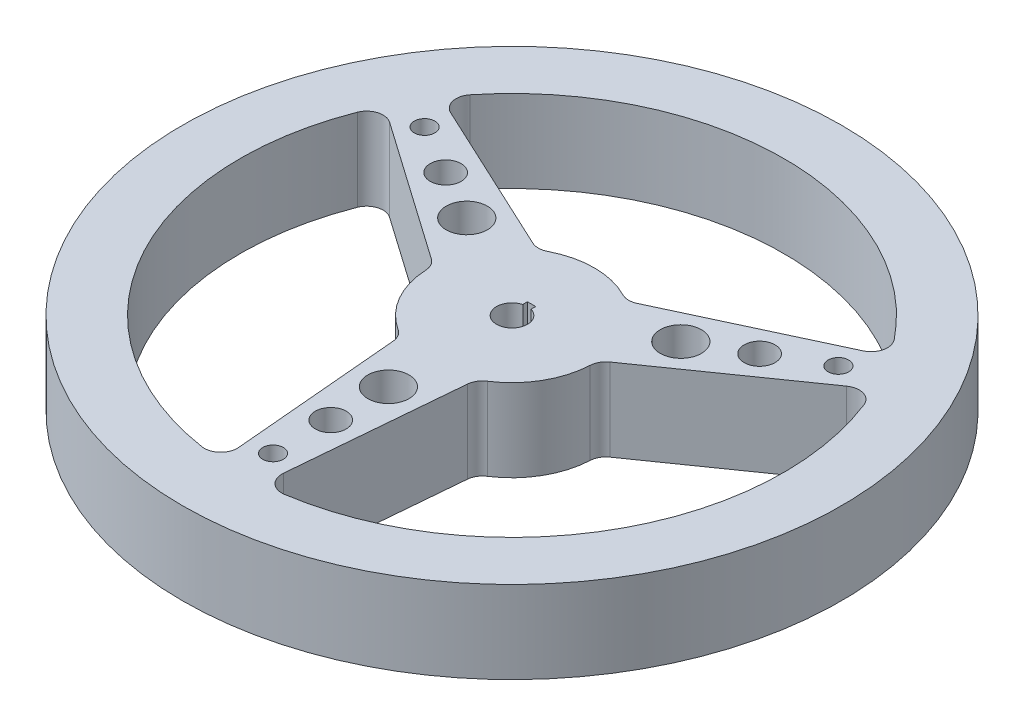
SolidWorks part; units mm, degrees
ref_plane "Front Plane" through (0, 0, 0) normal (0, 0, 1) x (1, 0, 0)
ref_plane "Top Plane" through (0, 0, 0) normal (0, 1, 0) x (1, 0, 0)
ref_plane "Right Plane" through (0, 0, 0) normal (1, 0, 0) x (0, 0, -1)
sketch "Sketch1" plane through (0, 0, 0) normal (0, 1, 0) x (1, 0, 0)
  line L0 (0, 0) -> (0, 3.0163) construction
  line L2 (-0.635, 2.295) -> (-0.635, 3.0163)
  line L3 (-0.635, 3.0163) -> (0.635, 3.0163)
  line L4 (0.635, 2.295) -> (0.635, 3.0163)
  circle A0 centre (0, 0) radius 50.8
  arc A1 (-0.635, 2.295) -> (0.635, 2.295) centre (0, 0) ccw
  dimension "D1" = 101.6
  dimension "D2" = 4.7625
  dimension "D4" = 1.27
  dimension "D5" = 3.0163
extrude "Boss-Extrude1" add sketch "Sketch1" along normal blind 12.7
sketch "Sketch2" plane through (0, 12.7, 0) normal (0, 1, 0) x (1, 0, 0)
  line L0 (3.175, -41.7896) -> (5.8447, -11.2752)
  line L1 (0, 0) -> (0, 33.1089) construction
  line L2 (-3.175, -41.7896) -> (-5.8447, -11.2752)
  line L3 (-34.6033, 23.6444) -> (-6.8423, 10.6992)
  line L4 (-37.7783, 18.1452) -> (-12.6869, 0.576)
  line L5 (37.7783, 18.1452) -> (12.6869, 0.576)
  line L6 (34.6033, 23.6444) -> (6.8423, 10.6992)
  circle A0 centre (0, 0) radius 12.7
  circle A1 centre (0, 0) radius 50.8
  circle A2 centre (0, 0) radius 50.8
  circle A3 centre (0, 0) radius 41.91
  circle A4 centre (0, -19.05) radius 3.175
  circle A5 centre (0, -27.94) radius 2.3813
  circle A6 centre (0, -36.83) radius 1.5875
  circle A7 centre (-16.4978, 9.525) radius 3.175
  circle A8 centre (-24.1967, 13.97) radius 2.3813
  circle A9 centre (-31.8957, 18.415) radius 1.5875
  circle A10 centre (16.4978, 9.525) radius 3.175
  circle A11 centre (24.1967, 13.97) radius 2.3813
  circle A12 centre (31.8957, 18.415) radius 1.5875
  point P41 (0, 0)
  dimension "D3" = 25.4
  dimension "D8" = 3.175
  dimension "D9" = 4.7625
  dimension "D10" = 6.35
  dimension "D4" = 175
  dimension "D5" = 6.35
  dimension "D6" = 8.89
  dimension "D7" = 8.89
  dimension "D11" = 19.05
  dimension "D1" = 0
  dimension "D2" = 8.89
  dimension "D12" = 3
extrude "Cut-Extrude1" cut sketch "Sketch2" against normal through all contours L4 A3 L2 A0 | L0 A3 L5 A0 | L1 A0 L6 A3 | A0 L1 A3 L3 | A7 | A8 | A9 | L1 A4 | A4 L1 | L1 A5 | A5 L1 | A6 L1 | A10 | A11 | A12
fillet "Fillet1" radius 2.54 12 edges at (37.7783, 6.35, -18.1452) (34.6033, 6.35, -23.6444) (-6.8423, 6.35, -10.6992) (6.8423, 6.35, -10.6992) (12.6869, 6.35, -0.576) (-12.6869, 6.35, -0.576) (-5.8447, 6.35, 11.2752) (-3.175, 6.35, 41.7896) (3.175, 6.35, 41.7896) (5.8447, 6.35, 11.2752) (-34.6033, 6.35, -23.6444) (-37.7783, 6.35, -18.1452)
